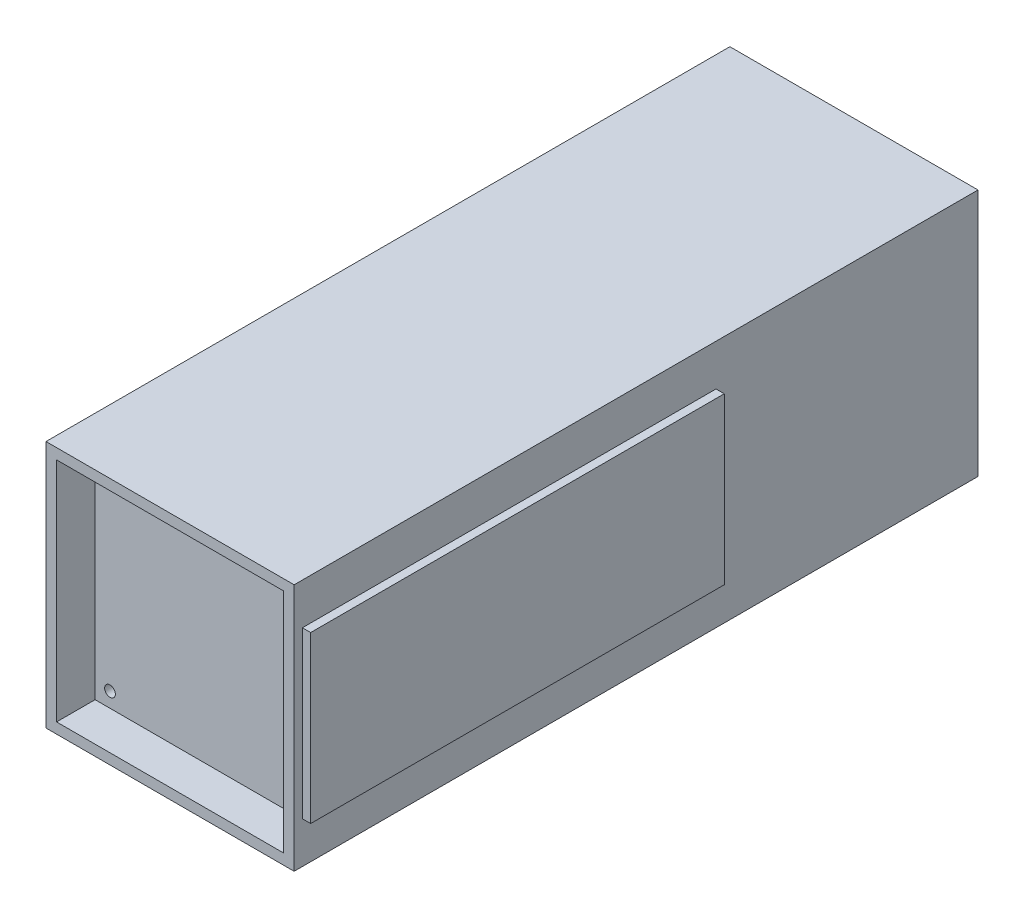
SolidWorks part; units mm, degrees
ref_plane "Front Plane" through (0, 0, 0) normal (0, 0, 1) x (1, 0, 0)
ref_plane "Top Plane" through (0, 0, 0) normal (0, 1, 0) x (1, 0, 0)
ref_plane "Right Plane" through (0, 0, 0) normal (1, 0, 0) x (0, 0, -1)
sketch "Sketch1" plane through (0, 0, 0) normal (0, 0, 1) x (1, 0, 0)
  line L0 (3.2512, 3.2512) -> (3.2512, 72.9488)
  line L1 (0, 0) -> (76.2, 0)
  line L2 (0, 0) -> (0, 76.2)
  line L3 (0, 76.2) -> (76.2, 76.2)
  line L4 (76.2, 0) -> (76.2, 76.2)
  line L5 (3.2512, 72.9488) -> (72.9488, 72.9488)
  line L6 (72.9488, 3.2512) -> (72.9488, 72.9488)
  line L7 (3.2512, 3.2512) -> (72.9488, 3.2512)
  dimension "D2" = 76.2
  dimension "D3" = 76.2
  dimension "D1" = 3.2512
extrude "Boss-Extrude1" add sketch "Sketch1" along normal blind 210
sketch "Sketch2" plane through (0, 0, 210) normal (0, 0, 1) x (1, 0, 0)
  line L0 (3.2512, 38.1) -> (72.9488, 38.1) construction
  line L1 (5.08, 5.08) -> (71.12, 5.08)
  line L2 (5.08, 5.08) -> (5.08, 71.12)
  line L3 (5.08, 71.12) -> (71.12, 71.12)
  line L4 (71.12, 5.08) -> (71.12, 71.12)
  line L5 (3.2512, 72.9488) -> (3.2512, 3.2512) construction
  line L6 (72.9488, 3.2512) -> (72.9488, 72.9488) construction
  line L7 (38.1, 72.9488) -> (38.1, 3.2512) construction
  line L8 (72.9488, 72.9488) -> (3.2512, 72.9488) construction
  line L9 (3.2512, 3.2512) -> (72.9488, 3.2512) construction
  point P16 (38.1, 5.08)
  point P17 (5.08, 38.1)
  dimension "D1" = 66.04
  dimension "D2" = 66.04
extrude "Boss-Extrude2" add sketch "Sketch2" against normal blind 3.048 from offset 10 separate body offset against normal yes
sketch "Sketch3" plane through (76.2, 0, 0) normal (1, 0, 0) x (0, 0, -1)
  line L0 (-210, 0) -> (-210, 76.2) construction
  line L1 (-207.46, 63.5) -> (-80.46, 63.5)
  line L2 (-207.46, 63.5) -> (-207.46, 12.7)
  line L3 (-207.46, 12.7) -> (-80.46, 12.7)
  line L4 (-80.46, 63.5) -> (-80.46, 12.7)
  line L6 (-210, 38.1) -> (-124.0046, 38.1) construction
  point P6 (-207.46, 38.1)
  dimension "D1" = 2.54
  dimension "D2" = 50.8
  dimension "D3" = 127
extrude "Boss-Extrude3" add sketch "Sketch3" along normal blind 2.54 separate body
sketch "Sketch4" plane through (0, 0, 196.952) normal (0, 0, -1) x (-1, 0, 0)
  line L1 (-3.2512, 3.2512) -> (-72.9488, 3.2512)
  line L2 (-3.2512, 3.2512) -> (-3.2512, 72.9488)
  line L3 (-3.2512, 72.9488) -> (-72.9488, 72.9488)
  line L4 (-72.9488, 3.2512) -> (-72.9488, 72.9488)
extrude "Boss-Extrude4" add sketch "Sketch4" along normal blind 1.27 separate body
ref_plane "Plane1" through (0, 0, 196.317) normal (0, 0, 1) x (1, 0, 0)
sketch "Sketch5" plane through (0, 0, 200) normal (0, 0, 1) x (1, 0, 0)
  line L0 (5.08, 5.08) -> (71.12, 5.08) construction
  line L1 (71.12, 5.08) -> (71.12, 71.12) construction
  line L2 (71.12, 71.12) -> (5.08, 5.08) construction
  line L3 (38.1, 38.1) -> (36.1598, 40.0402) construction
  circle A0 centre (66.548, 9.652) radius 1.524
  circle A1 centre (66.548, 66.548) radius 1.524
  circle A2 centre (9.652, 66.548) radius 1.524
  circle A3 centre (9.652, 9.652) radius 1.524
  point P21 (38.1, 38.1)
  dimension "D1" = 3.048
  dimension "D2" = 4.572
  dimension "D3" = 4.572
  dimension "D4" = 4
extrude "Cut-Extrude1" cut sketch "Sketch5" against normal up to next (3.048 mm away)
mirror "Mirror2" about plane through (0, 0, 196.317) normal (0, 0, 1) of bodies 106 102
sketch "Sketch6" plane through (0, 0, 192.634) normal (0, 0, -1) x (-1, 0, 0)
  line L0 (-5.08, 5.08) -> (-71.12, 71.12) construction
  line L1 (-71.12, 71.12) -> (-38.1, 38.1) construction
  circle A0 centre (-66.548, 9.652) radius 2.159
  circle A1 centre (-66.548, 9.652) radius 2.9972
  circle A2 centre (-66.548, 66.548) radius 2.9972
  circle A3 centre (-66.548, 66.548) radius 2.159
  circle A4 centre (-9.652, 66.548) radius 2.9972
  circle A5 centre (-9.652, 66.548) radius 2.159
  circle A6 centre (-9.652, 9.652) radius 2.9972
  circle A7 centre (-9.652, 9.652) radius 2.159
  point P21 (-38.1, 38.1)
  dimension "D1" = 5.9944
  dimension "D2" = 4.318
  dimension "D3" = 4
extrude "Boss-Extrude5" add sketch "Sketch6" along normal blind 10.16 separate body
sketch "Sketch8" plane through (0, 0, 192.634) normal (0, 0, -1) x (-1, 0, 0)
  line L4 (-5.08, 5.08) -> (-5.08, 71.12)
  line L5 (-5.08, 71.12) -> (-71.12, 71.12)
  line L6 (-71.12, 71.12) -> (-71.12, 5.08)
  line L7 (-71.12, 5.08) -> (-5.08, 5.08)
  line L8 (-5.08, 5.08) -> (-5.08, 71.12)
  line L9 (-5.08, 71.12) -> (-71.12, 71.12)
  line L10 (-71.12, 71.12) -> (-71.12, 5.08)
  line L11 (-71.12, 5.08) -> (-5.08, 5.08)
  circle A0 centre (-9.652, 9.652) radius 2.159 construction
  circle A1 centre (-66.548, 9.652) radius 2.159 construction
  circle A2 centre (-66.548, 66.548) radius 2.159 construction
  circle A3 centre (-9.652, 66.548) radius 2.159 construction
  circle A4 centre (-9.652, 9.652) radius 2.159
  circle A5 centre (-66.548, 9.652) radius 2.159
  circle A6 centre (-66.548, 66.548) radius 2.159
  circle A7 centre (-9.652, 66.548) radius 2.159
  dimension "D1" = 0
extrude "Boss-Extrude6" add sketch "Sketch8" along normal blind 3.048 from offset 10.16 separate body
hole_wizard "M4x0.7 Tapped Hole1" positions "Sketch14" profile "Sketch13" tap size "M4x0.7" standard "ANSI Metric"
sketch "Sketch14" plane through (0, 0, 200) normal (0, 0, 1) x (1, 0, 0)
  point P0 (9.652, 66.548)
  point P3 (66.548, 66.548)
  point P6 (66.548, 9.652)
  point P9 (9.652, 9.652)
sketch "Sketch13" plane through (9.652, 66.548, 200) normal (1, 0, 0) x (0, -1, 0)
  line L0 (0, 0) -> (0, 4.0384)
  line L1 (0, 4.0384) -> (1.65, 3.047)
  line L2 (1.65, 3.047) -> (1.65, 0)
  line L5 (1.65, 0) -> (0, 0)
  line L10 (0, 4.0384) -> (-1.65, 3.047) construction
  line L11 (0, -6.35) -> (0, 107.95) construction
  dimension "Tap Drill Dia." = 3.3
  dimension "Tap Drill Depth" = 3.047
  dimension "Drill Angle" = 118
cosmetic thread "Hole Thread9" parameters "D1"=3.048, "D2"=4
cosmetic thread "Hole Thread10" parameters "D1"=3.048, "D2"=4
cosmetic thread "Hole Thread11" parameters "D1"=3.048, "D2"=4
cosmetic thread "Hole Thread12" parameters "D1"=3.048, "D2"=4
ref_plane "Plane2" through (0, 91.2, 0) normal (0, 1, 0) x (1, 0, 0)
ref_plane "Plane3" through (0, -15, 0) normal (0, -1, 0) x (-1, 0, 0)
ref_plane "Plane4" through (0, 38.1, 0) normal (0, -1, 0) x (-1, 0, 0)
